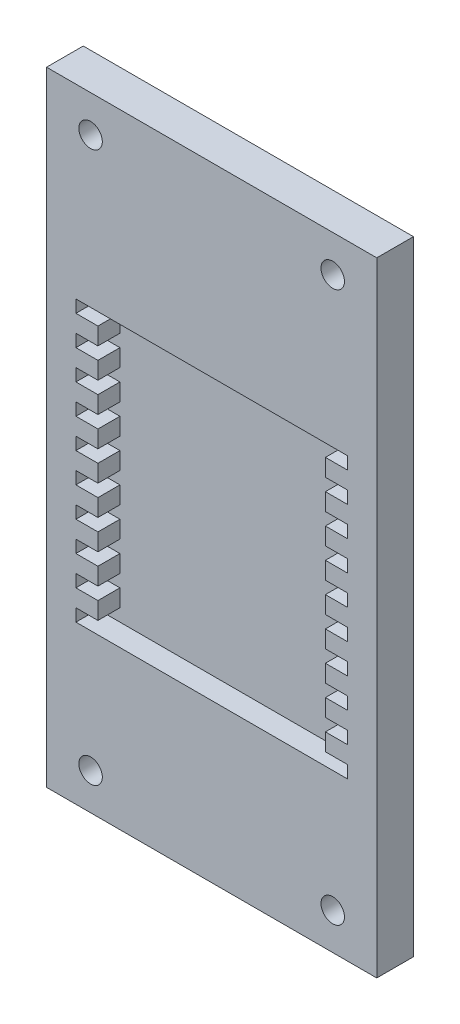
SolidWorks part; units mm, degrees
ref_plane "Ebene vorne" through (0, 0, 0) normal (0, 0, 1) x (1, 0, 0)
ref_plane "Ebene oben" through (0, 0, 0) normal (0, 1, 0) x (1, 0, 0)
ref_plane "Ebene rechts" through (0, 0, 0) normal (1, 0, 0) x (0, 0, -1)
sketch "Skizze1" plane through (0, 0, 0) normal (0, 0, 1) x (1, 0, 0)
  line L1 (0, 0) -> (45, 0)
  line L2 (0, 0) -> (0, 85)
  line L3 (0, 85) -> (45, 85)
  line L4 (45, 0) -> (45, 85)
  dimension "D1" = 45
  dimension "D2" = 85
extrude "Aufsatz-Linear austragen1" add sketch "Skizze1" along normal blind 5
sketch "Skizze6" plane through (0, 0, 5) normal (0, 0, 1) x (1, 0, 0)
  line L0 (0, 85) -> (0, 0) construction
  line L1 (45, 85) -> (0, 85) construction
  line L2 (45, 0) -> (45, 85) construction
  line L3 (0, 0) -> (45, 0) construction
  circle A0 centre (6, 80) radius 1.6
  circle A1 centre (39, 80) radius 1.6
  circle A2 centre (39, 5) radius 1.6
  circle A3 centre (6, 5) radius 1.6
  dimension "D8" = 6
  dimension "D9" = 3.2
  dimension "D10" = 3.2
  dimension "D11" = 3.2
  dimension "D12" = 3.2
  dimension "D1" = 6
  dimension "D2" = 5
  dimension "D3" = 5
  dimension "D4" = 6
  dimension "D5" = 5
  dimension "D6" = 6
  dimension "D7" = 5
extrude "Schnitt-Linear austragen2" cut sketch "Skizze6" against normal blind 3
sketch "Skizze7" plane through (0, 0, 5) normal (0, 0, 1) x (1, 0, 0)
  line L0 (45, 85) -> (0, 85) construction
  line L1 (4, 59.65) -> (41, 59.65)
  line L2 (4, 59.65) -> (4, 57.95)
  line L3 (4, 57.95) -> (41, 57.95)
  line L4 (41, 59.65) -> (41, 57.95)
  line L5 (45, 0) -> (45, 85) construction
  line L6 (0, 0) -> (45, 0) construction
  line L7 (4, 55.6) -> (41, 55.6)
  line L8 (4, 55.6) -> (4, 53.9)
  line L9 (4, 53.9) -> (41, 53.9)
  line L10 (41, 55.6) -> (41, 53.9)
  line L11 (4, 51.55) -> (41, 51.55)
  line L12 (4, 51.55) -> (4, 49.85)
  line L13 (4, 49.85) -> (41, 49.85)
  line L14 (41, 51.55) -> (41, 49.85)
  line L15 (4, 47.5) -> (41, 47.5)
  line L16 (4, 47.5) -> (4, 45.8)
  line L17 (4, 45.8) -> (41, 45.8)
  line L18 (41, 47.5) -> (41, 45.8)
  line L19 (4, 43.45) -> (41, 43.45)
  line L20 (4, 43.45) -> (4, 41.75)
  line L21 (4, 41.75) -> (41, 41.75)
  line L22 (41, 43.45) -> (41, 41.75)
  line L23 (4, 39.4) -> (41, 39.4)
  line L24 (4, 39.4) -> (4, 37.7)
  line L25 (4, 37.7) -> (41, 37.7)
  line L26 (41, 39.4) -> (41, 37.7)
  line L27 (4, 35.35) -> (41, 35.35)
  line L28 (4, 35.35) -> (4, 33.65)
  line L29 (4, 33.65) -> (41, 33.65)
  line L30 (41, 35.35) -> (41, 33.65)
  line L31 (4, 31.3) -> (41, 31.3)
  line L32 (4, 31.3) -> (4, 29.6)
  line L33 (4, 29.6) -> (41, 29.6)
  line L34 (41, 31.3) -> (41, 29.6)
  line L35 (4, 27.25) -> (41, 27.25)
  line L36 (4, 27.25) -> (4, 25.55)
  line L37 (4, 25.55) -> (41, 25.55)
  line L38 (41, 27.25) -> (41, 25.55)
  line L39 (4, 23.2) -> (41, 23.2)
  line L40 (4, 23.2) -> (4, 21.5)
  line L41 (4, 21.5) -> (41, 21.5)
  line L42 (41, 23.2) -> (41, 21.5)
  dimension "D1" = 25.35
  dimension "D2" = 1.7
  dimension "D3" = 4
  dimension "D4" = 37
  dimension "D5" = 1.7
  dimension "D6" = 1.7
  dimension "D7" = 1.7
  dimension "D8" = 1.7
  dimension "D9" = 1.7
  dimension "D10" = 1.7
  dimension "D11" = 1.7
  dimension "D12" = 1.7
  dimension "D13" = 1.7
  dimension "D14" = 21.5
  dimension "D15" = 2.35
  dimension "D16" = 2.35
  dimension "D17" = 2.35
  dimension "D18" = 2.35
  dimension "D19" = 2.35
  dimension "D20" = 2.35
  dimension "D21" = 2.35
  dimension "D22" = 2.35
  dimension "D23" = 2.35
  dimension "D24" = 37
  dimension "D25" = 37
  dimension "D26" = 37
  dimension "D27" = 37
  dimension "D28" = 37
  dimension "D29" = 37
  dimension "D30" = 37
  dimension "D31" = 37
  dimension "D32" = 37
  dimension "D33" = 4
  dimension "D34" = 4
  dimension "D35" = 4
  dimension "D36" = 4
  dimension "D37" = 4
  dimension "D38" = 4
  dimension "D39" = 4
  dimension "D40" = 4
  dimension "D41" = 4
extrude "Schnitt-Linear austragen3" cut sketch "Skizze7" against normal blind 10
sketch "Skizze8" plane through (0, 0, 5) normal (0, 0, 1) x (1, 0, 0)
  line L0 (41, 59.65) -> (4, 59.65) construction
  line L1 (7, 59.65) -> (38, 59.65)
  line L2 (7, 59.65) -> (7, 21.5)
  line L3 (7, 21.5) -> (38, 21.5)
  line L4 (38, 59.65) -> (38, 21.5)
  line L5 (4, 21.5) -> (41, 21.5) construction
  line L6 (41, 57.95) -> (41, 59.65) construction
  line L7 (4, 43.45) -> (4, 41.75) construction
  dimension "D1" = 3
  dimension "D2" = 3
extrude "Schnitt-Linear austragen4" cut sketch "Skizze8" against normal blind 10
sketch "Skizze9" plane through (0, 0, 0) normal (0, 0, -1) x (-1, 0, 0)
  line L1 (-41.3422, 60.8413) -> (-3.2909, 60.8413)
  line L2 (-41.3422, 60.8413) -> (-41.3422, 20.0732)
  line L3 (-41.3422, 20.0732) -> (-3.2909, 20.0732)
  line L4 (-3.2909, 60.8413) -> (-3.2909, 20.0732)
extrude "Aufsatz-Linear austragen2" add sketch "Skizze9" against normal blind 2
